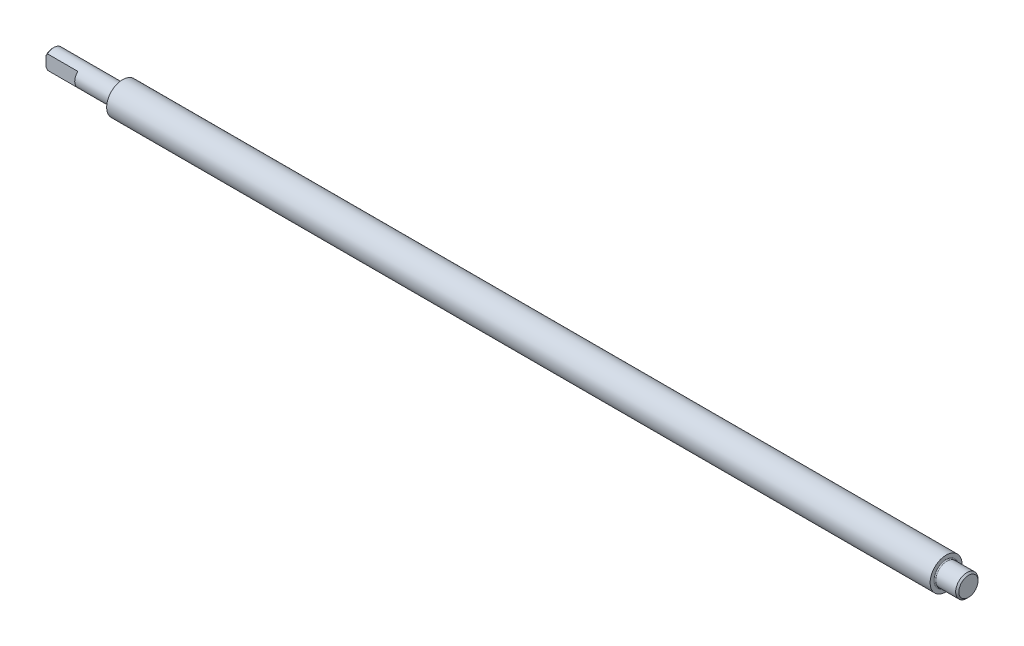
SolidWorks part; units mm, degrees
ref_plane "Front Plane" through (0, 0, 0) normal (0, 0, 1) x (1, 0, 0)
ref_plane "Top Plane" through (0, 0, 0) normal (0, 1, 0) x (1, 0, 0)
ref_plane "Right Plane" through (0, 0, 0) normal (1, 0, 0) x (0, 0, -1)
sketch "Sketch1" plane through (0, 0, 0) normal (0, 0, 1) x (1, 0, 0)
  line L0 (22, 5) -> (22, 0)
  line L1 (22, 0) -> (280, 0)
  line L2 (280, 0) -> (280, 5)
  line L3 (280, 5) -> (22, 5)
  line L4 (22, 0) -> (280, 0) construction
  dimension "D1" = 258
  dimension "D2" = 5
revolve "Revolve1" add sketch "Sketch1" angle 360 about L4
sketch "Sketch2" plane through (22, 0, 0) normal (-1, 0, 0) x (0, 0, 1)
  circle A0 centre (0, 0) radius 3
  dimension "D1" = 6
extrude "Boss-Extrude1" add sketch "Sketch2" along normal blind 22
sketch "Sketch3" plane through (0, 0, 0) normal (-1, 0, 0) x (0, 0, 1)
  line L0 (2, 2.2361) -> (2, -2.2361)
  arc A0 (2, -2.2361) -> (2, 2.2361) centre (0, 0) ccw
  circle A1 centre (0, 0) radius 3 construction
  dimension "D1" = 3
  dimension "D2" = 2
  dimension "D3" = 2.2361
  dimension "D4" = 2.2361
extrude "Cut-Extrude1" cut sketch "Sketch3" against normal blind 10
sketch "Sketch4" plane through (280, 0, 0) normal (1, 0, 0) x (0, 0, -1)
  circle A0 centre (0, 0) radius 3.5
  dimension "D1" = 7
extrude "Boss-Extrude2" add sketch "Sketch4" along normal blind 7
chamfer "Chamfer1" distance 0.5 angle 45 2 edges at (287, 0, -3.5) (0, 0, -3)
fillet "Fillet1" radius 0.3 2 edges at (22, 0, 3) (280, 0, -3.5)
